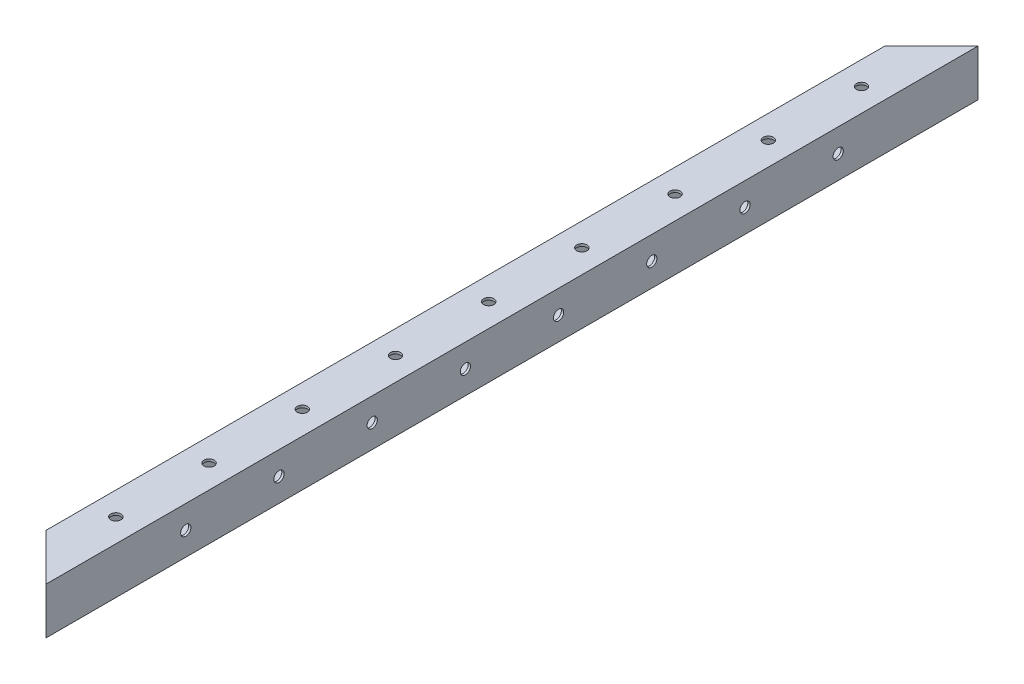
SolidWorks part; units mm, degrees
ref_plane "前视基准面" through (0, 0, 0) normal (0, 0, 1) x (1, 0, 0)
ref_plane "上视基准面" through (0, 0, 0) normal (0, 1, 0) x (1, 0, 0)
ref_plane "右视基准面" through (0, 0, 0) normal (1, 0, 0) x (0, 0, -1)
sketch "草图1" plane through (0, 0, 0) normal (0, 1, 0) x (1, 0, 0)
  line L2 (40, 200) -> (80, 200)
  line L3 (200, 40) -> (200, 80)
  line L5 (200, -40) -> (200, -80)
  line L6 (120, -200) -> (160, -200)
  line L9 (-40, -200) -> (-80, -200)
  line L10 (-200, -40) -> (-200, -80)
  line L13 (-200, 40) -> (-200, 80)
  line L14 (-40, 200) -> (-80, 200)
  line L17 (200, 205) -> (205, 205)
  line L18 (205, 200) -> (205, 205)
  line L21 (205, -200) -> (205, -205)
  line L22 (200, -205) -> (205, -205)
  line L25 (-200, -205) -> (-205, -205)
  line L26 (-205, -200) -> (-205, -205)
  line L29 (-205, 200) -> (-205, 205)
  line L30 (-200, 205) -> (-205, 205)
  line L31 (-200, 205) -> (-160, 205)
  line L32 (-160, 205) -> (-160, 200)
  line L33 (-120, 200) -> (-120, 205)
  line L34 (-120, 205) -> (-80, 205)
  line L35 (-80, 205) -> (-80, 200)
  line L36 (-80, 200) -> (-40, 200)
  line L37 (-40, 200) -> (-40, 205)
  line L38 (-40, 205) -> (40, 205)
  line L39 (40, 205) -> (40, 200)
  line L40 (80, 200) -> (80, 205)
  line L41 (80, 205) -> (120, 205)
  line L42 (120, 205) -> (120, 200)
  line L43 (120, 200) -> (160, 200)
  line L44 (160, 200) -> (160, 205)
  line L45 (160, 205) -> (200, 205)
  line L46 (205, 160) -> (200, 160)
  line L47 (200, 120) -> (205, 120)
  line L48 (205, 120) -> (205, 80)
  line L49 (205, 80) -> (200, 80)
  line L50 (200, 80) -> (200, 40)
  line L51 (200, 40) -> (205, 40)
  line L52 (205, 40) -> (205, -40)
  line L53 (205, -40) -> (200, -40)
  line L54 (200, -80) -> (205, -80)
  line L55 (205, -80) -> (205, -120)
  line L56 (205, -120) -> (200, -120)
  line L57 (200, -120) -> (200, -160)
  line L58 (200, -160) -> (205, -160)
  line L59 (205, 200) -> (205, 160)
  line L60 (205, -160) -> (205, -200)
  line L61 (160, -205) -> (160, -200)
  line L62 (120, -200) -> (120, -205)
  line L63 (120, -205) -> (80, -205)
  line L64 (80, -205) -> (80, -200)
  line L65 (80, -200) -> (40, -200)
  line L66 (40, -200) -> (40, -205)
  line L67 (40, -205) -> (-40, -205)
  line L68 (-40, -205) -> (-40, -200)
  line L69 (-80, -200) -> (-80, -205)
  line L70 (-80, -205) -> (-120, -205)
  line L71 (-120, -205) -> (-120, -200)
  line L72 (-120, -200) -> (-160, -200)
  line L73 (-160, -200) -> (-160, -205)
  line L74 (200, -205) -> (160, -205)
  line L75 (-160, -205) -> (-200, -205)
  line L76 (-205, -160) -> (-200, -160)
  line L77 (-200, -120) -> (-205, -120)
  line L78 (-205, -120) -> (-205, -80)
  line L79 (-205, -80) -> (-200, -80)
  line L80 (-200, -80) -> (-200, -40)
  line L81 (-200, -40) -> (-205, -40)
  line L82 (-205, -40) -> (-205, 40)
  line L83 (-205, 40) -> (-200, 40)
  line L84 (-200, 80) -> (-205, 80)
  line L85 (-205, 80) -> (-205, 120)
  line L86 (-205, 120) -> (-200, 120)
  line L87 (-200, 120) -> (-200, 160)
  line L88 (-200, 160) -> (-205, 160)
  line L89 (-205, -200) -> (-205, -160)
  line L90 (-205, 160) -> (-205, 200)
  line L91 (-120, 200) -> (-160, 200)
  line L92 (-200, 120) -> (-200, 160)
  line L93 (-200, -120) -> (-200, -160)
  line L94 (200, -120) -> (200, -160)
  line L95 (200, 120) -> (200, 160)
  line L96 (120, 200) -> (160, 200)
  circle A0 centre (-190, 0) radius 2.2
  circle A1 centre (-190, 40) radius 2.2
  circle A2 centre (-190, 80) radius 2.2
  circle A3 centre (-190, 120) radius 2.2
  circle A4 centre (-190, 160) radius 2.2
  circle A5 centre (-190, -160) radius 2.2
  circle A6 centre (-190, -120) radius 2.2
  circle A7 centre (-190, -80) radius 2.2
  circle A8 centre (-190, -40) radius 2.2
  circle A9 centre (0, 190) radius 2.2
  circle A10 centre (40, 190) radius 2.2
  circle A11 centre (80, 190) radius 2.2
  circle A12 centre (120, 190) radius 2.2
  circle A13 centre (160, 190) radius 2.2
  circle A14 centre (-160, 190) radius 2.2
  circle A15 centre (-120, 190) radius 2.2
  circle A16 centre (-80, 190) radius 2.2
  circle A17 centre (-40, 190) radius 2.2
  circle A18 centre (190, 0) radius 2.2
  circle A19 centre (190, -40) radius 2.2
  circle A20 centre (190, -80) radius 2.2
  circle A21 centre (190, -120) radius 2.2
  circle A22 centre (190, -160) radius 2.2
  circle A23 centre (190, 160) radius 2.2
  circle A24 centre (190, 120) radius 2.2
  circle A25 centre (190, 80) radius 2.2
  circle A26 centre (190, 40) radius 2.2
  circle A27 centre (0, -190) radius 2.2
  circle A28 centre (-40, -190) radius 2.2
  circle A29 centre (-80, -190) radius 2.2
  circle A30 centre (-120, -190) radius 2.2
  circle A31 centre (-160, -190) radius 2.2
  circle A32 centre (160, -190) radius 2.2
  circle A33 centre (120, -190) radius 2.2
  circle A34 centre (80, -190) radius 2.2
  circle A35 centre (40, -190) radius 2.2
  point P83 (0, 0)
  point P99 (0, 0)
  point P170 (0, 0)
extrude "凸台-拉伸1" add sketch "草图1" along normal blind 5 contours L47 L95 L46 L59 L18 L17 L45 L44 L43 L42 L41 L40 L2 L39 L38 L37 L14 L35 L34 L33 L91 L32 L31 L30 L29 L90 L88 L87 L86 L85 L84 L13 L83 L82 L81 L10 L79 L78 L77 L93 L76 L89 L26 L25 L75 L73 L72 L71 L70 L69 L9
sketch "草图2" plane through (0, 5, 0) normal (0, 1, 0) x (1, 0, 0)
  line L0 (-262.3388, 278.3326) -> (303.269, 271.2532)
  line L1 (-200, -200) -> (-200, -160)
  line L3 (-180, -160) -> (-180, -180)
  line L4 (-180, -180) -> (-200, -200)
  line L5 (-200, 200) -> (-180, 180)
  line L6 (-180, 180) -> (-180, -160)
  line L7 (-200, -160) -> (-200, 200)
  line L8 (-262.3388, 278.3326) -> (-269.2198, -271.4324)
  line L9 (303.269, 271.2532) -> (296.388, -278.5118)
  line L10 (-269.2198, -271.4324) -> (296.388, -278.5118)
  line L11 (-200, 200) -> (-180, 200)
  line L12 (-180, 200) -> (-180, 180)
  line L13 (-180, -180) -> (-180, -200)
  line L14 (-180, -200) -> (-200, -200)
extrude "切除-拉伸2" cut sketch "草图2" against normal blind 5 contours L8 L10 L9 L0 L13 L14 L1 L7 L11 L12 L6 L3
sketch "草图3" plane through (0, 0, 200) normal (0, 0, 1) x (1, 0, 0)
  line L0 (-200, 5) -> (-200, 4)
  line L1 (-200, 0) -> (-200, 5) construction
  line L2 (-200, 4) -> (-180, 4)
  line L3 (-200, 4) -> (-200, -15)
  line L4 (-180, 4) -> (-180, -15)
  line L5 (-200, -15) -> (-180, -15)
  line L6 (-180, 0) -> (-180, 5) construction
  point P10 (0, 0)
  line M4 (-200, 0) -> (-180, 0)
extrude "凸台-拉伸2" add sketch "草图3" against normal blind 400 contours L3 L5 L4 M4
sketch "草图4" plane through (0, 0, 200) normal (0, 0, 1) x (1, 0, 0)
  line L0 (-200, 5) -> (-199, 5)
  line L1 (-200, 5) -> (-200, 4)
  line L2 (-199, 5) -> (-199, 4)
  line L3 (-200, 4) -> (-199, 4)
  line L4 (-180, 5) -> (-200, 5) construction
  line L5 (-199, 4) -> (-181, 4)
  line L6 (-199, 4) -> (-199, -14)
  line L7 (-181, 4) -> (-181, -14)
  line L8 (-199, -14) -> (-181, -14)
extrude "切除-拉伸4" cut sketch "草图4" against normal blind 400 contours L6 L8 L7 L5
sketch "草图5" plane through (0, 5, 0) normal (0, 1, 0) x (1, 0, 0)
  line L0 (-200, 200) -> (-180, 200)
  line L2 (-180, 200) -> (-200, 180)
  line L3 (-200, -200) -> (-200, 200) construction
  line L4 (-200, 180) -> (-200, 200)
  line L5 (-180, -200) -> (-200, -180)
  line L6 (-200, -180) -> (-180, -180)
  line L7 (-180, 200) -> (-180, -200) construction
  line L8 (-180, -180) -> (-180, -200)
  line L9 (-180, -200) -> (-200, -200) construction
  line L10 (-200, -180) -> (-200, -200)
  line L11 (-200, -200) -> (-180, -200)
  line M2 (-200, 200) -> (-200, -200)
  line M3 (-200, -200) -> (-180, -200)
extrude "切除-拉伸5" cut sketch "草图5" against normal blind 400 contours L5 M3 M2 | L0 L2 L4
sketch "草图6" plane through (0, 5, 0) normal (0, 1, 0) x (1, 0, 0)
  circle A0 centre (-190, 160) radius 2.2
  circle A1 centre (-190, 120) radius 2.2
  circle A2 centre (-190, 80) radius 2.2
  circle A3 centre (-190, 40) radius 2.2
  circle A4 centre (-190, 0) radius 2.2
  circle A5 centre (-190, -40) radius 2.2
  circle A6 centre (-190, -80) radius 2.2
  circle A7 centre (-190, -120) radius 2.2
  circle A8 centre (-190, -160) radius 2.2
  dimension "D1" = 9
extrude "切除-拉伸6" cut sketch "草图6" against normal blind 400
sketch "草图7" plane through (-200, 0, 0) normal (-1, 0, 0) x (0, 0, 1)
  circle A0 centre (-140, -5) radius 2.2
  circle A1 centre (-100, -5) radius 2.2
  circle A2 centre (-60, -5) radius 2.2
  circle A3 centre (-20, -5) radius 2.2
  circle A4 centre (20, -5) radius 2.2
  circle A5 centre (60, -5) radius 2.2
  circle A6 centre (100, -5) radius 2.2
  circle A7 centre (140, -5) radius 2.2
extrude "切除-拉伸7" cut sketch "草图7" against normal blind 40
